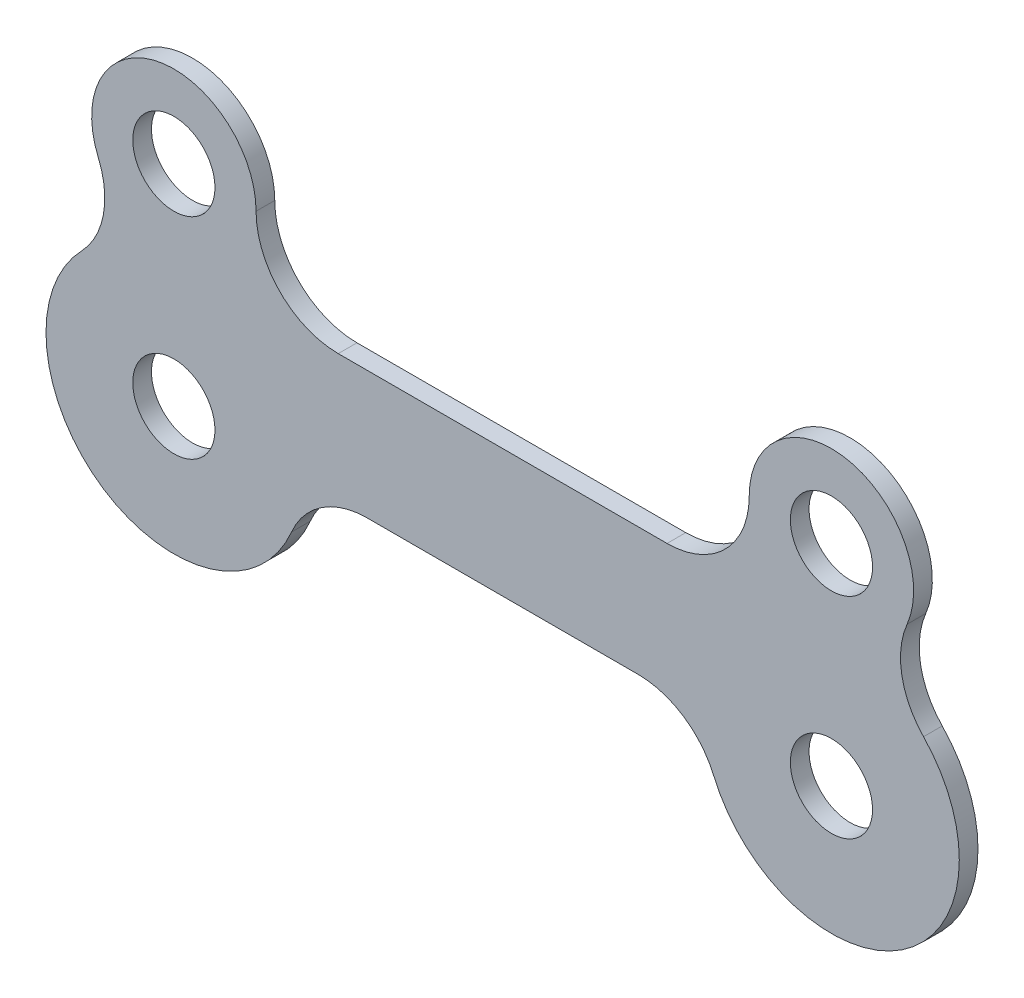
SolidWorks part; units mm, degrees
ref_plane "Front Plane" through (0, 0, 0) normal (0, 0, 1) x (1, 0, 0)
ref_plane "Top Plane" through (0, 0, 0) normal (0, 1, 0) x (1, 0, 0)
ref_plane "Right Plane" through (0, 0, 0) normal (1, 0, 0) x (0, 0, -1)
sketch "Sketch1" plane through (0, 0, 0) normal (0, 0, 1) x (1, 0, 0)
  line L0 (5.5562, 0) -> (23.0188, 0)
  line L1 (0, 5.5562) -> (28.575, 5.5562)
  line L2 (0, 5.5562) -> (0, -5.5562) construction
  line L3 (0, -5.5562) -> (28.575, -5.5562) construction
  line L4 (28.575, 5.5562) -> (28.575, -5.5562) construction
  line L5 (0, 5.5562) -> (28.575, 5.5562) construction
  line L6 (0, 5.5562) -> (0, -10.3188) construction
  line L7 (0, -10.3188) -> (28.575, -10.3188) construction
  line L8 (28.575, 5.5562) -> (28.575, -10.3188) construction
  line L9 (28.575, 0) -> (35.6916, -0.6226) construction
  line L10 (28.575, 9.1281) -> (28.575, 0) construction
  circle A0 centre (0, 0) radius 5.5562 construction
  circle A1 centre (28.575, 0) radius 5.5562 construction
  arc A2 (0, 5.5562) -> (0, -5.5562) centre (0, 0) ccw
  arc A3 (28.575, -5.5562) -> (28.575, 5.5562) centre (28.575, 0) ccw
  circle A4 centre (0, 0) radius 1.7859
  circle A5 centre (28.575, 0) radius 1.7859
  arc A6 (0, -5.5562) -> (5.5562, 0) centre (0, 0) ccw
  arc A7 (23.0188, 0) -> (28.575, -5.5562) centre (28.575, 0) ccw
  circle A10 centre (0, 9.1281) radius 3.5719
  circle A12 centre (28.575, 9.1281) radius 1.7859
  circle A15 centre (0, 9.1281) radius 1.7859
  circle A16 centre (21.4312, 9.1281) radius 3.5719
  circle A17 centre (28.575, 9.1281) radius 3.5719
  circle A18 centre (7.1437, 9.1281) radius 3.5719
  circle A20 centre (35.1491, 6.3327) radius 3.5719
  circle A21 centre (8.4003, -3.5719) radius 3.5719
  circle A22 centre (20.1747, -3.5719) radius 3.5719
  circle A25 centre (0, 0) radius 9.1281 construction
  circle A26 centre (-6.5741, 6.3327) radius 3.5719
  dimension "D1" = 28.575
  dimension "D2" = 11.1125
  dimension "D3" = 3.5719
  dimension "D5" = 95
  dimension "D6" = 7.1437
  dimension "D7" = 3.5719
  dimension "D4" = 15.875
extrude "Boss-Extrude1" add sketch "Sketch1" along normal blind 0.8128
